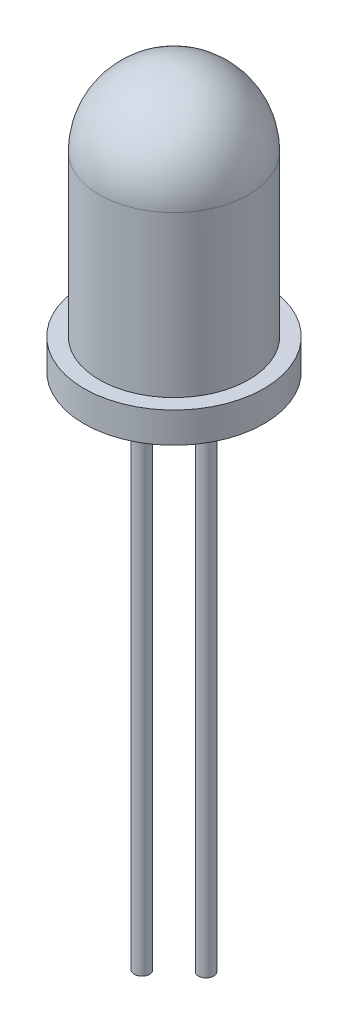
SolidWorks part; units mm, degrees
material "Bronce de aluminio"
ref_plane "Front Plane" through (0, 0, 0) normal (0, 0, 1) x (1, 0, 0)
ref_plane "Top Plane" through (0, 0, 0) normal (0, 1, 0) x (1, 0, 0)
ref_plane "Right Plane" through (0, 0, 0) normal (1, 0, 0) x (0, 0, -1)
sketch "Croquis1" plane through (0, 0, 0) normal (0, 1, 0) x (1, 0, 0)
  circle A0 centre (0, 0) radius 2.95
  dimension "D1" = 5.9
extrude "Saliente-Extruir1" add sketch "Croquis1" along normal blind 1
sketch "Croquis2" plane through (0, 0, 0) normal (0, 0, 1) x (1, 0, 0)
  line L0 (0, 0) -> (0, 8.7) construction
  line L1 (0, 1) -> (-2.45, 1)
  line L2 (2.95, 1) -> (-2.95, 1) construction
  line L3 (-2.45, 1) -> (-2.45, 6.25)
  line L4 (0, 1) -> (0, 8.7)
  arc A0 (0, 8.7) -> (-2.45, 6.25) centre (0, 6.25) ccw
  dimension "D3" = 4.9
  dimension "D1" = 8.7
  dimension "D2" = 2.45
revolve "Revolución1" add sketch "Croquis2" angle 360 about L0
sketch "Croquis4" plane through (0, 0, 0) normal (0, -1, 0) x (-1, 0, 0)
  circle A0 centre (0, 0) radius 2.45
  dimension "D1" = 4.9
extrude "Cortar-Extruir1" cut sketch "Croquis4" against normal blind 0.5
sketch "Croquis5" plane through (0, 0.5, 0) normal (0, -1, 0) x (1, 0, 0)
  line L0 (-1.05, 0) -> (1.05, 0) construction
  circle A0 centre (-1.05, 0) radius 0.25
  circle A1 centre (1.05, 0) radius 0.25
  point P3 (0, 0)
  dimension "D2" = 0.5
  dimension "D3" = 0.5
  dimension "D1" = 2.1
extrude "Saliente-Extruir2" add sketch "Croquis5" along normal blind 18 and the other way blind 2
sketch "Croquis6" plane through (0, -17.5, 0) normal (0, -1, 0) x (1, 0, 0)
  circle A1 centre (1.05, 0) radius 0.25
  circle A2 centre (1.05, 0) radius 0.25
  dimension "D1" = 0
extrude "Cortar-Extruir2" cut sketch "Croquis6" against normal blind 1
